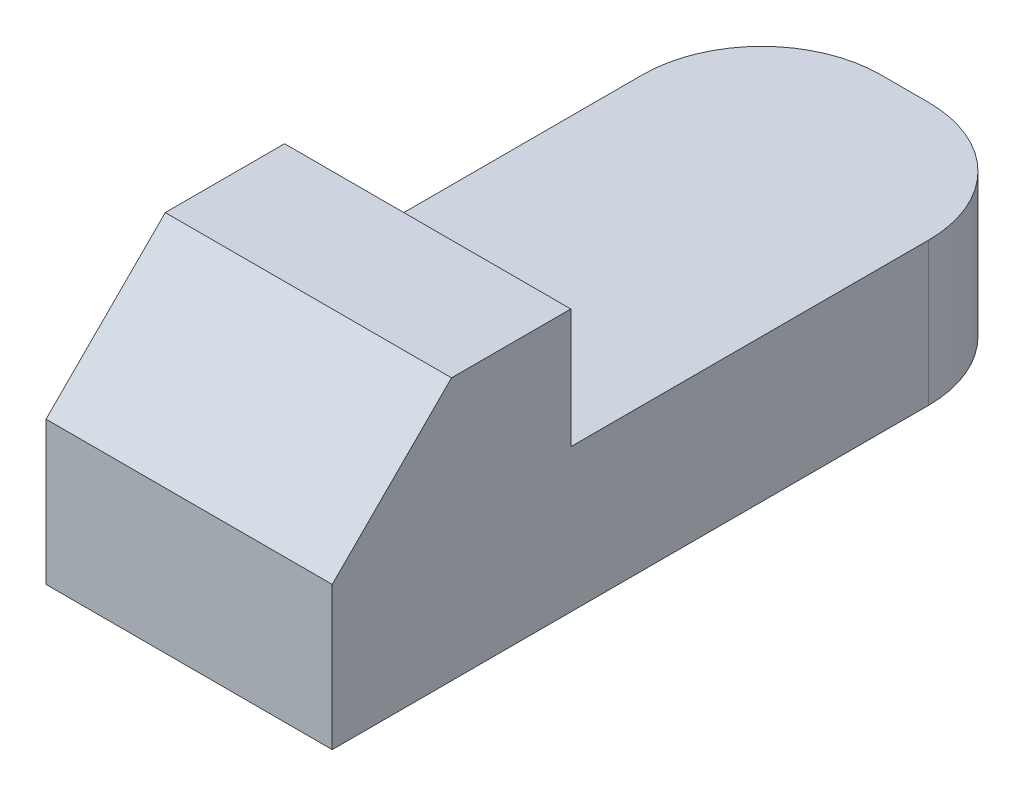
SolidWorks part; units mm, degrees
material "Cast Carbon Steel"
ref_plane "Front Plane" through (0, 0, 0) normal (0, 0, 1) x (1, 0, 0)
ref_plane "Top Plane" through (0, 0, 0) normal (0, 1, 0) x (1, 0, 0)
ref_plane "Right Plane" through (0, 0, 0) normal (1, 0, 0) x (0, 0, -1)
sketch "Sketch1" plane through (0, 0, 0) normal (0, 0, 1) x (1, 0, 0)
  line L1 (-6, -3) -> (6, -3)
  line L2 (-6, -3) -> (-6, 3)
  line L3 (-6, 3) -> (6, 3)
  line L4 (6, -3) -> (6, 3)
  line L5 (-6, -3) -> (6, 3) construction
  line L6 (-6, 3) -> (6, -3) construction
  point P0 (0, 0)
  dimension "D1" = 12
  dimension "D2" = 6
extrude "Boss-Extrude1" add sketch "Sketch1" against normal blind 30
sketch "Sketch2" plane through (0, 3, 0) normal (0, 1, 0) x (1, 0, 0)
  line L0 (6, 30) -> (6, 0) construction
  line L1 (-6, 0) -> (6, 0)
  line L2 (-6, 0) -> (-6, 10)
  line L3 (-6, 10) -> (6, 10)
  line L4 (6, 0) -> (6, 10)
  dimension "D1" = 10
extrude "Boss-Extrude2" add sketch "Sketch2" along normal blind 5
sketch "Sketch3" plane through (6, 0, 0) normal (1, 0, 0) x (0, 0, -1)
  line L0 (5, 8) -> (0, 3)
  line L1 (0, 8) -> (10, 8) construction
  line L2 (0, -3) -> (0, 8) construction
  line L3 (0, 3) -> (0, 8)
  line L4 (0, 8) -> (5, 8)
  dimension "D1" = 45
extrude "Cut-Extrude1" cut sketch "Sketch3" against normal through all
fillet "Fillet1" radius 5 2 edges at (-6, 0, -30) (6, 0, -30)
